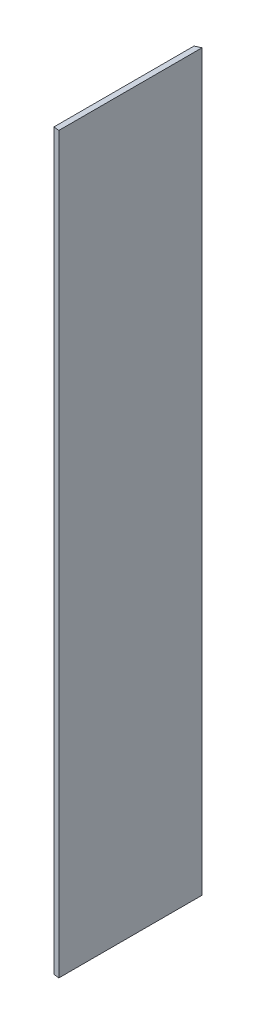
SolidWorks part; units mm, degrees
ref_plane "Спереди" through (0, 0, 0) normal (0, 0, 1) x (1, 0, 0)
ref_plane "Сверху" through (0, 0, 0) normal (0, 1, 0) x (1, 0, 0)
ref_plane "Справа" through (0, 0, 0) normal (1, 0, 0) x (0, 0, -1)
sketch "Эскиз1" plane through (0, 0, 0) normal (0, 1, 0) x (1, 0, 0)
  line L0 (1.0264, -5.5532) -> (1.0264, -107.3249)
  line L1 (1.0264, -107.3249) -> (5.0264, -107.8388)
  line L2 (5.0264, -107.8388) -> (5.0264, -3.7635)
  line L3 (5.0264, -3.7635) -> (1.0264, -5.5532)
  line L4 (0.2179, -107.1085) -> (4.8056, -108.3365) construction
  dimension "D1" = 4
extrude "Вытянуть1" add sketch "Эскиз1" along normal up to surface (533.2137 mm away)
